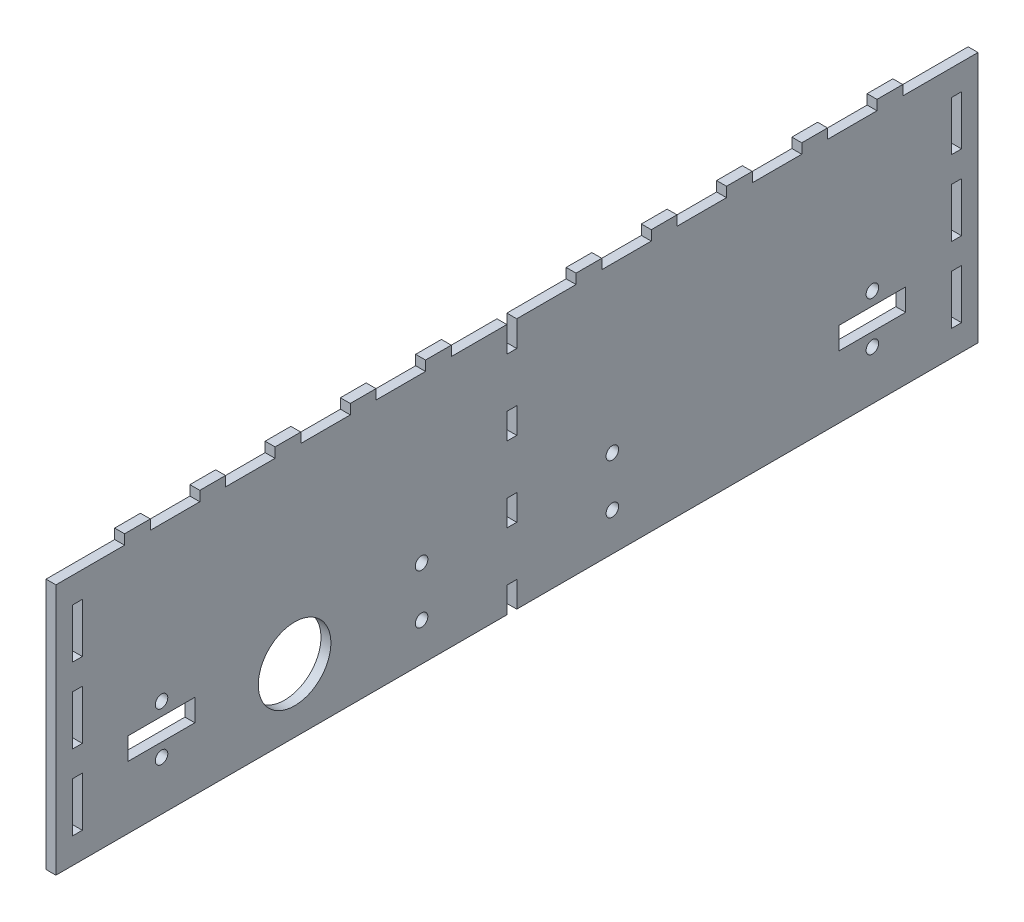
SolidWorks part; units mm, degrees
material "ENPH 253 Hardboard"
ref_plane "Front Plane" through (0, 0, 0) normal (0, 0, 1) x (1, 0, 0)
ref_plane "Top Plane" through (0, 0, 0) normal (0, 1, 0) x (1, 0, 0)
ref_plane "Right Plane" through (0, 0, 0) normal (1, 0, 0) x (0, 0, -1)
sketch "Sketch1" plane through (0, 0, 0) normal (1, 0, 0) x (0, 0, -1)
  line L1 (-139.7, 38.1) -> (139.7, 38.1)
  line L2 (-139.7, 38.1) -> (-139.7, -38.1)
  line L3 (-139.7, -38.1) -> (139.7, -38.1)
  line L4 (139.7, 38.1) -> (139.7, -38.1)
  line L5 (-139.7, 38.1) -> (139.7, -38.1) construction
  line L6 (-139.7, -38.1) -> (139.7, 38.1) construction
  point P0 (0, 0)
  dimension "D1" = 279.4
  dimension "D2" = 76.2
extrude "Boss-Extrude1" add sketch "Sketch1" against normal blind 3 contours L2 L3 L4 L1
sketch "Sketch3" plane through (-3, 0, 0) normal (-1, 0, 0) x (0, 0, 1)
  line L0 (-139.7, 38.1) -> (-139.7, -38.1) construction
  line L1 (139.7, 38.1) -> (139.7, -38.1) construction
  line L2 (139.7, 38.1) -> (-139.7, 38.1) construction
  line L3 (134.7, 30.3) -> (131.7, 30.3)
  line L4 (134.7, 30.3) -> (134.7, 15.3)
  line L5 (134.7, 15.3) -> (131.7, 15.3)
  line L6 (131.7, 30.3) -> (131.7, 15.3)
  line L7 (139.7, 38.1) -> (139.7, -38.1) construction
  circle A0 centre (69.85, 0) radius 50.8 construction
  circle A1 centre (-69.85, 0) radius 50.8 construction
  dimension "D1" = 101.6
  dimension "D2" = 101.6
  dimension "D3" = 69.85
  dimension "D4" = 69.85
  dimension "D5" = 15
  dimension "D6" = 7.8
  dimension "D7" = 5
  dimension "D8" = 3
extrude "Cut-Extrude1" cut sketch "Sketch3" against normal through all
pattern_linear "LPattern1" count 3 spacing 22.8 along (0, -1, 0) of "Cut-Extrude1"
mirror "Mirror1" about plane through (0, 0, 0) normal (0, 0, 1) of "LPattern1", "Cut-Extrude1"
sketch "Sketch6" plane through (-3, 0, 0) normal (-1, 0, 0) x (0, 0, 1)
  line L0 (139.7, 38.1) -> (-139.7, 38.1) construction
  line L1 (0.06, 38.1) -> (3.06, 38.1)
  line L2 (0.06, 38.1) -> (0.06, 30.3)
  line L3 (0.06, 30.3) -> (3.06, 30.3)
  line L4 (3.06, 38.1) -> (3.06, 30.3)
  dimension "D1" = 136.64
  dimension "D2" = 3
  dimension "D3" = 7.8
extrude "Cut-Extrude2" cut sketch "Sketch6" against normal through all
pattern_linear "LPattern2" count 4 spacing 22.8 along (0, -1, 0) of "Cut-Extrude2"
sketch "Sketch8" plane through (0, 38.1, 0) normal (0, 1, 0) x (1, 0, 0)
  line L0 (0, -139.7) -> (0, -3.06) construction
  line L1 (0, 116.9) -> (-3, 116.9)
  line L2 (0, 116.9) -> (0, 109.1)
  line L3 (0, 109.1) -> (-3, 109.1)
  line L4 (-3, 116.9) -> (-3, 109.1)
  line L5 (-3, -139.7) -> (-3, -3.06) construction
  line L7 (-3, 139.7) -> (0, 139.7) construction
  dimension "D1" = 22.8
  dimension "D2" = 7.8
extrude "Boss-Extrude2" add sketch "Sketch8" along normal blind 3
pattern_linear "LPattern4" count 11 spacing 22.8 along (0, 0, 1) skipping (5, 0) of "Boss-Extrude2"
sketch "Sketch9" plane through (-3, 0, 0) normal (-1, 0, 0) x (0, 0, 1)
  line L0 (139.7, -38.1) -> (3.06, -38.1) construction
  line L1 (3.06, -15.3) -> (3.06, -7.5) construction
  circle A0 centre (67.38, -18.8) radius 11
  dimension "D1" = 22
  dimension "D2" = 19.3
  dimension "D3" = 64.32
extrude "Cut-Extrude3" cut sketch "Sketch9" against normal through all contours A0
hole_wizard "#6 Clearance Hole1" positions "Sketch10" profile "Sketch11" hole size "#6" standard "ANSI Inch" end condition up to next
sketch "Sketch10" plane through (0, 0, 0) normal (1, 0, 0) x (0, 0, -1)
  circle A0 centre (28.9, -26.55) radius 1.8987 construction
  point P0 (28.9, -26.55)
  point P2 (28.9, -11.55)
  point P5 (-28.9, -11.55)
  point P8 (-28.9, -26.55)
sketch "Sketch11" plane through (0, -26.55, -28.9) normal (0, 1, 0) x (0, 0, -1)
  line L0 (0, 0) -> (0, 3)
  line L1 (0, 3) -> (1.8986, 3)
  line L2 (1.8986, 3) -> (1.8986, 0)
  line L5 (1.8986, 0) -> (0, 0)
  line L11 (0, -6.35) -> (0, 107.95) construction
  dimension "Thru Hole Dia." = 3.7973
  dimension "Thru Hole Depth" = 3
sketch "Sketch12" plane through (-3, 0, 0) normal (-1, 0, 0) x (0, 0, 1)
  line L0 (-134.7, -30.3) -> (-134.7, -15.3) construction
  line L1 (-117.7, -19.05) -> (-97.7, -19.05) construction
  line L2 (-117.7, -19.05) -> (-117.7, -12.55) construction
  line L3 (-117.7, -12.55) -> (-97.7, -12.55) construction
  line L4 (-97.7, -19.05) -> (-97.7, -12.55) construction
  line L5 (0.06, -38.1) -> (-139.7, -38.1) construction
  line L6 (-117.8, -19.15) -> (-97.6, -19.15)
  line L7 (-97.6, -19.15) -> (-97.6, -12.45)
  line L8 (-117.8, -12.45) -> (-97.6, -12.45)
  line L9 (-117.8, -19.15) -> (-117.8, -12.45)
  line L10 (-139.7, 8.007) -> (139.7, 8.007) construction
  line L11 (-139.7, 38.1) -> (-139.7, -38.1) construction
  line L12 (139.7, 38.1) -> (139.7, -38.1) construction
  line L13 (0, 8.007) -> (0, -38.1) construction
  line L14 (97.7, -19.05) -> (97.7, -12.55) construction
  line L15 (117.7, -12.55) -> (97.7, -12.55) construction
  line L16 (117.7, -19.05) -> (117.7, -12.55) construction
  line L17 (117.7, -19.05) -> (97.7, -19.05) construction
  line L18 (117.8, -19.15) -> (117.8, -12.45)
  line L19 (117.8, -12.45) -> (97.6, -12.45)
  line L20 (97.6, -19.15) -> (97.6, -12.45)
  line L21 (117.8, -19.15) -> (97.6, -19.15)
  point P21 (-107.7, -8.45)
  point P22 (-107.7, -23.15)
  point P31 (0, 0)
  point P32 (-107.7, -12.45)
  point P33 (0, 0)
  point P34 (107.7, -23.15)
  point P35 (107.7, -8.45)
  dimension "D1" = 17
  dimension "D2" = 19.05
  dimension "D3" = 6.5
  dimension "D4" = 20
  dimension "D6" = 4
  dimension "D7" = 4
  dimension "D5" = 0.1
extrude "Cut-Extrude4" cut sketch "Sketch12" against normal up to next
hole_wizard "#6 Clearance Hole2" positions "Sketch13" profile "Sketch14" hole size "#6" standard "ANSI Inch" end condition through all
sketch "Sketch13" plane through (-3, 0, 0) normal (-1, 0, 0) x (0, 0, 1)
  line L0 (-117.8, -15.8) -> (117.8, -15.8) construction
  line L1 (-117.8, -12.45) -> (-117.8, -19.15) construction
  line L2 (117.8, -19.15) -> (117.8, -12.45) construction
  line L4 (0, -15.8) -> (0, -97.249) construction
  line L7 (-117.8, -19.15) -> (-97.6, -19.15) construction
  line L8 (-117.8, -19.15) -> (-97.6, -19.15) construction
  point P0 (-107.7, -23.15)
  point P35 (0, 0)
  point P36 (-107.7, -19.15)
  point P37 (-107.7, -8.45)
  point P38 (0, 0)
  point P39 (107.7, -23.15)
  point P40 (107.7, -8.45)
  dimension "D1" = 4
sketch "Sketch14" plane through (-3, -23.15, -107.7) normal (0, 1, 0) x (0, 0, 1)
  line L0 (0, 0) -> (0, 3)
  line L1 (0, 3) -> (1.8986, 3)
  line L2 (1.8986, 3) -> (1.8986, 0)
  line L5 (1.8986, 0) -> (0, 0)
  line L11 (0, -6.35) -> (0, 107.95) construction
  dimension "Thru Hole Dia." = 3.7973
  dimension "Thru Hole Depth" = 3
equation "\"D4@Sketch3\"=\"D3@Sketch3\""
